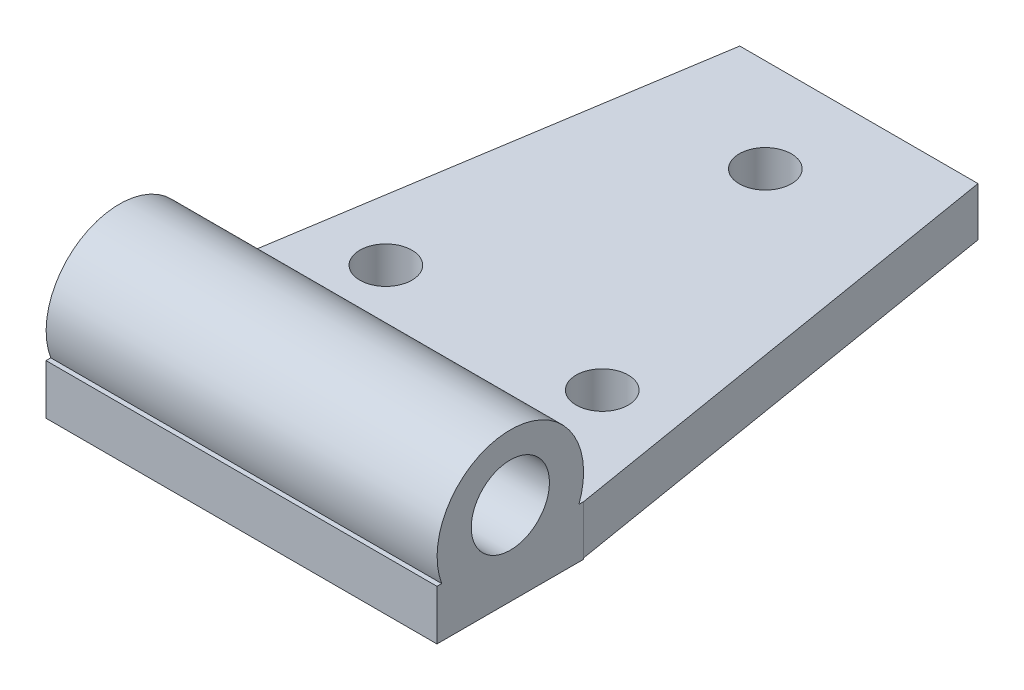
SolidWorks part; units mm, degrees
ref_plane "Front Plane" through (0, 0, 0) normal (0, 0, 1) x (1, 0, 0)
ref_plane "Top Plane" through (0, 0, 0) normal (0, 1, 0) x (1, 0, 0)
ref_plane "Right Plane" through (0, 0, 0) normal (1, 0, 0) x (0, 0, -1)
sketch "Sketch1" plane through (0, 0, 0) normal (0, 1, 0) x (1, 0, 0)
  line L0 (0, 0) -> (38.1, 0)
  line L2 (18.8637, 0) -> (18.8637, 46.0502) construction
  line L3 (30.4715, 46.0502) -> (7.2559, 46.0502)
  line L4 (0, 0) -> (7.2559, 46.0502)
  line L5 (30.4715, 46.0502) -> (38.1, 0)
  point P8 (18.8637, 46.0502)
extrude "Boss-Extrude1" add sketch "Sketch1" along normal blind 4.7498 contours L4 L3 L5 L0
sketch "Sketch2" plane through (0, 4.7498, 0) normal (0, 1, 0) x (1, 0, 0)
  line L0 (18.8637, 46.0502) -> (18.8637, 36.9316) construction
  line L1 (30.4715, 46.0502) -> (7.2559, 46.0502) construction
  line L2 (19.05, 0) -> (19.05, 10.3124) construction
  line L3 (0, 0) -> (38.1, 0) construction
  line L4 (29.591, 10.3124) -> (8.509, 10.3124) construction
  circle A0 centre (18.8637, 36.9316) radius 2.54
  circle A1 centre (8.509, 10.3124) radius 2.54
  circle A2 centre (29.591, 10.3124) radius 2.54
  point P11 (19.05, 10.3124)
extrude "Cut-Extrude1" cut sketch "Sketch2" against normal blind 4.7498
sketch "Sketch3" plane through (0, 0, 0) normal (0, 0, 1) x (1, 0, 0)
  line L0 (0, 4.7498) -> (38.1, 4.7498)
  line L1 (0, 4.7498) -> (0, -0.1172)
  line L2 (38.1, 4.7498) -> (38.1, -0.1172)
  line L3 (0, -0.1172) -> (38.1, -0.1172)
extrude "Boss-Extrude2" add sketch "Sketch3" along normal blind 14.3002
sketch "Sketch4" plane through (38.1, 0, 0) normal (1, 0, 0) x (0, 0, -1)
  line L0 (-7.1501, -0.1172) -> (-7.1501, 7.2488) construction
  line L1 (-14.3002, -0.1172) -> (0, -0.1172) construction
  circle A0 centre (-7.1501, 7.2488) radius 7.1374
extrude "Boss-Extrude3" add sketch "Sketch4" against normal up to surface (38.1 mm away) up to face at (0, 1.8531, 5.7201)
sketch "Sketch5" plane through (38.1, 0, 0) normal (1, 0, 0) x (0, 0, -1)
  line L0 (-7.1501, 14.3862) -> (-7.1501, 8.0362) construction
  arc A0 (-0.4645, 4.7498) -> (-13.8357, 4.7498) centre (-7.1501, 7.2488) ccw construction
  circle A1 centre (-7.1501, 8.0362) radius 3.81
extrude "Cut-Extrude2" cut sketch "Sketch5" against normal blind 43.2562
